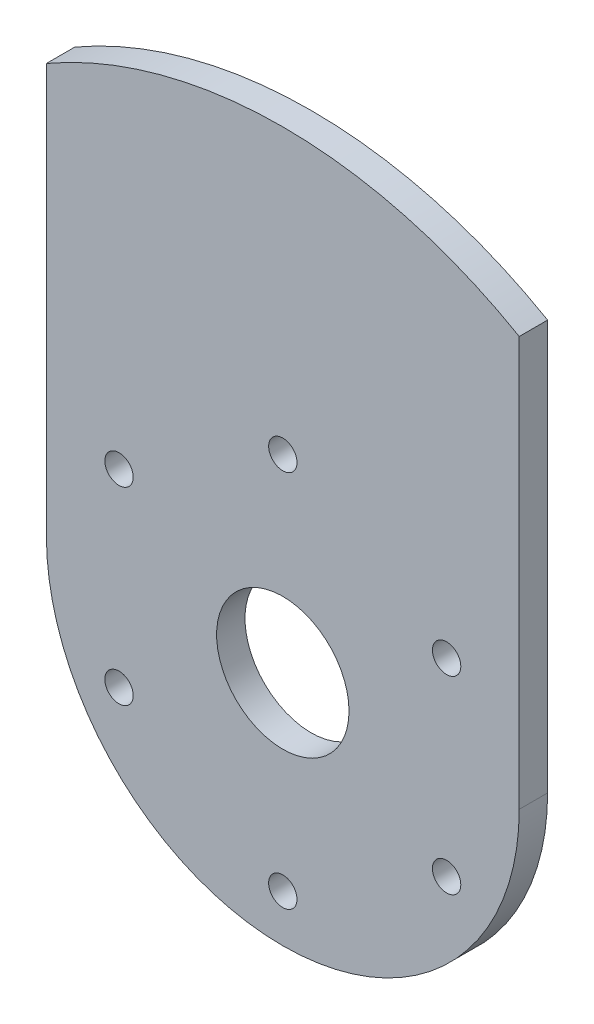
SolidWorks part; units mm, degrees
ref_plane "Plan de face" through (0, 0, 0) normal (0, 0, 1) x (1, 0, 0)
ref_plane "Plan de dessus" through (0, 0, 0) normal (0, 1, 0) x (1, 0, 0)
ref_plane "Plan de droite" through (0, 0, 0) normal (1, 0, 0) x (0, 0, -1)
sketch "Esquisse1" plane through (0, 0, 0) normal (0, 0, 1) x (1, 0, 0)
  circle A0 centre (0, 0) radius 50
  circle A1 centre (0, 0) radius 7
extrude "Boss.-Extru.1" add sketch "Esquisse1" along normal blind 3
sketch "Esquisse2" plane through (0, 0, 3) normal (0, 0, 1) x (1, 0, 0)
  line L0 (-25, 0) -> (25, 0)
  line L1 (-25, 0) -> (-25, 50.4793)
  line L2 (25, 0) -> (25, 50.4793)
  line L3 (-25, 50.4793) -> (25, 50.4793)
  circle A0 centre (0, 20) radius 1.5
  circle A1 centre (17.3205, 10) radius 1.5
  circle A2 centre (17.3205, -10) radius 1.5
  circle A3 centre (0, -20) radius 1.5
  circle A4 centre (-17.3205, -10) radius 1.5
  circle A5 centre (-17.3205, 10) radius 1.5
  circle A6 centre (0, 0) radius 25
  point P4 (0, 0)
  point P12 (0, 0)
  point P33 (0, 0)
  circle M3 centre (0, 0) radius 50
  dimension "D1" = 20
  dimension "D2" = 6
extrude "Enlèv. mat.-Extru.1" cut sketch "Esquisse2" against normal through all contours A6 L1 L2 M3 | A3 | A4 | A5 | A2 | A0 | A1
